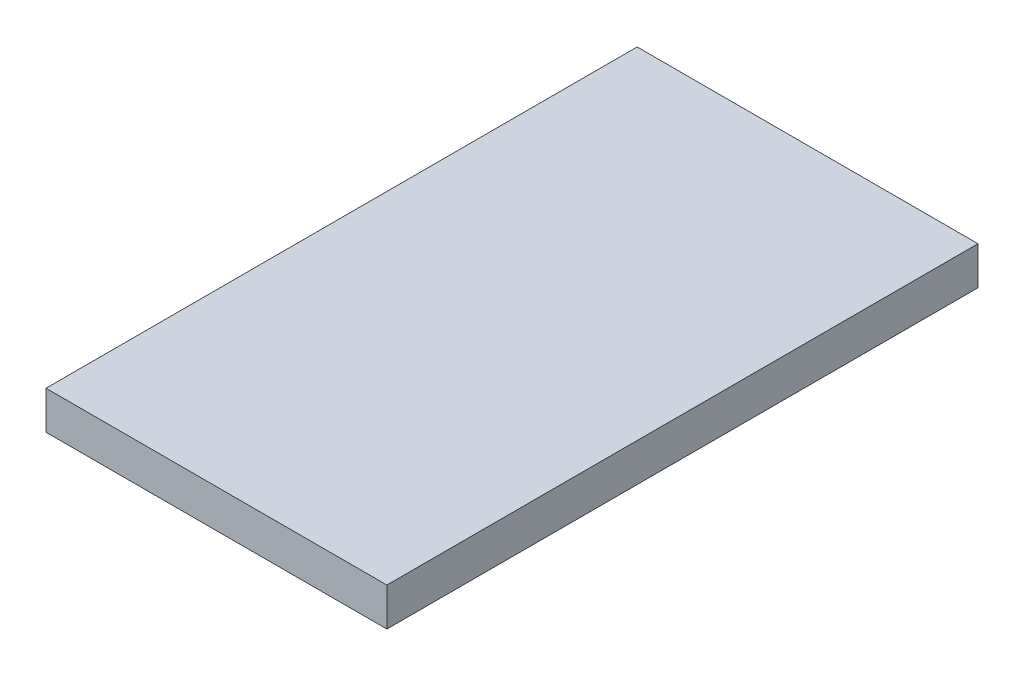
SolidWorks part; units mm, degrees
ref_plane "前视基准面" through (0, 0, 0) normal (0, 0, 1) x (1, 0, 0)
ref_plane "上视基准面" through (0, 0, 0) normal (0, 1, 0) x (1, 0, 0)
ref_plane "右视基准面" through (0, 0, 0) normal (1, 0, 0) x (0, 0, -1)
sketch "草图1" plane through (0, 0, 0) normal (0, 1, 0) x (1, 0, 0)
  line L0 (-25.6755, 0) -> (17.4682, 0) construction
  line L1 (-7.15, 12.4) -> (7.15, 12.4)
  line L2 (-7.15, 12.4) -> (-7.15, -12.4)
  line L3 (-7.15, -12.4) -> (7.15, -12.4)
  line L4 (7.15, 12.4) -> (7.15, -12.4)
  line L5 (0, 17.8263) -> (0, -18.2214) construction
  dimension "D1" = 14.3
  dimension "D2" = 24.8
extrude "凸台-拉伸1" add sketch "草图1" along normal blind 1.6
sketch "草图2" plane through (0, 1.6, 0) normal (0, 1, 0) x (1, 0, 0)
  line L0 (4.5191, 10.9416) -> (1.4849, 10.9416)
  line L1 (1.4849, 10.9416) -> (1.4849, 7.4787)
  line L2 (1.4849, 7.4787) -> (0.7593, 7.4787)
  line L3 (0.7593, 7.4787) -> (0.7593, 10.9416)
  line L4 (0.7593, 10.9416) -> (0, 10.9416)
  line L5 (0, 10.9416) -> (0, 7.4787)
  line L6 (0, 7.4787) -> (-0.8567, 7.4787)
  line L7 (-0.8567, 7.4787) -> (-0.8567, 10.9416)
  line L8 (-0.8567, 10.9416) -> (-1.8132, 10.9416)
  line L9 (-1.8132, 10.9416) -> (-1.8132, 7.4787)
  line L10 (-1.8132, 7.4787) -> (-2.6707, 7.4787)
  line L11 (-2.6707, 7.4787) -> (-2.6707, 10.9416)
  line L12 (-2.6707, 10.9416) -> (-3.8909, 10.9416)
  line L13 (-3.8909, 10.9416) -> (-3.8909, 6.2584)
  line L14 (-3.8909, 6.2584) -> (3.002, 6.2584)
